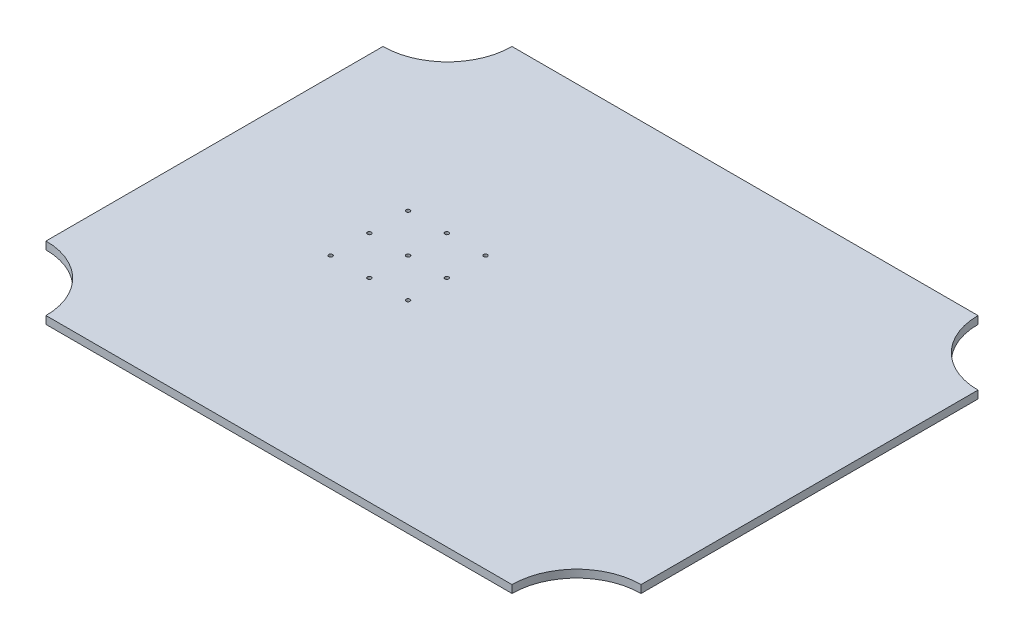
SolidWorks part; units mm, degrees
material "有机玻璃 (TM) GS 丙烯酸铸钣"
ref_plane "前视基准面" through (0, 0, 0) normal (0, 0, 1) x (1, 0, 0)
ref_plane "上视基准面" through (0, 0, 0) normal (0, 1, 0) x (1, 0, 0)
ref_plane "右视基准面" through (0, 0, 0) normal (1, 0, 0) x (0, 0, -1)
other "Configuration Table"
sketch "草图1" plane through (0, 0, 0) normal (0, 1, 0) x (1, 0, 0)
  line L0 (-398.7057, 0) -> (467.8173, 0) construction
  line L1 (-100, 180.5) -> (261, 180.5)
  line L2 (-150, 130.5) -> (-150, -130.5)
  line L3 (-100, -180.5) -> (261, -180.5)
  line L4 (311, 130.5) -> (311, -130.5)
  line L7 (0, 316.7734) -> (0, -278.6958) construction
  line L8 (-30, 180.5) -> (-30, -180.5) construction
  line L9 (30, 180.5) -> (30, -180.5) construction
  arc A0 (-150, 130.5) -> (-100, 180.5) centre (-150, 180.5) ccw
  arc A1 (261, 180.5) -> (311, 130.5) centre (311, 180.5) ccw
  arc A2 (311, -130.5) -> (261, -180.5) centre (311, -180.5) ccw
  arc A3 (-100, -180.5) -> (-150, -130.5) centre (-150, -180.5) ccw
  circle A4 centre (-30, 0) radius 1.5
  circle A5 centre (-30, 30) radius 1.5
  circle A6 centre (0, 30) radius 1.5
  circle A7 centre (30, 30) radius 1.5
  circle A8 centre (0, 0) radius 1.5
  circle A9 centre (30, 0) radius 1.5
  circle A10 centre (30, -30) radius 1.5
  circle A11 centre (0, -30) radius 1.5
  circle A12 centre (-30, -30) radius 1.5
  point P0 (0, 0)
  point P13 (-150, 0)
  dimension "D3" = 100
  dimension "D6" = 3
  dimension "D1" = 361
  dimension "D2" = 461
  dimension "D4" = 30
  dimension "D5" = 30
  dimension "D7" = 60
  dimension "D8" = 60
  dimension "D9" = 60
  dimension "D10" = 150
extrude "凸台-拉伸1" add sketch "草图1" along normal blind 6
